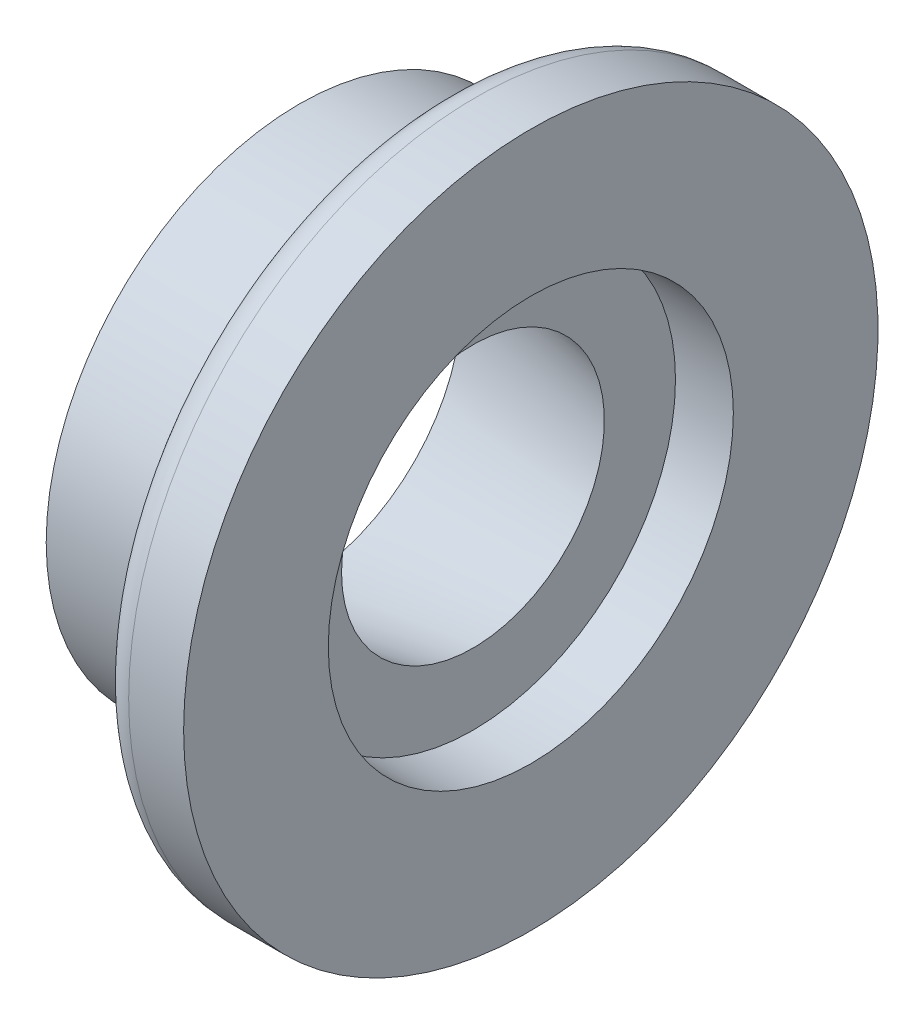
SolidWorks part; units mm, degrees
ref_plane "XZ (Face)" through (0, 0, 0) normal (0, 0, 1) x (1, 0, 0)
ref_plane "XY (Dessus)" through (0, 0, 0) normal (0, 1, 0) x (1, 0, 0)
ref_plane "YZ (Droite)" through (0, 0, 0) normal (1, 0, 0) x (0, 0, -1)
sketch "Esquisse2" plane through (0, 0, 0) normal (0, 0, 1) x (1, 0, 0)
  line L0 (39, 4.692) -> (33, 5.75) construction
  line L1 (39.85, 4.5422) -> (33.85, 5.6001)
  line L2 (39.85, 4.5422) -> (39.85, 7)
  line L3 (39.85, 7) -> (41.85, 7)
  line L4 (41.85, 7) -> (41.85, 12)
  line L5 (41.85, 12) -> (38.85, 12)
  line L6 (38.85, 12) -> (38.85, 8.75)
  line L7 (38.85, 8.75) -> (33.85, 8.75)
  line L8 (33.85, 8.75) -> (33.85, 5.6001)
  line L9 (33.75, -6.7494) -> (33.75, 6.75) construction
  line L11 (0, 0) -> (70.9337, 0) construction
  line L12 (17.5, 0) -> (6, 0) construction
  dimension "D1" = 0.1
  dimension "D2" = 14
  dimension "D3" = 24
  dimension "D4" = 2
  dimension "D5" = 8
  dimension "D6" = 3
  dimension "D7" = 17.5
revolve "Base-Révolution" add sketch "Esquisse2" angle 360 about L11
fillet "Congé1" radius 1.1 2 edges at (38.85, 0, 8.75) (38.85, 0, 12)
